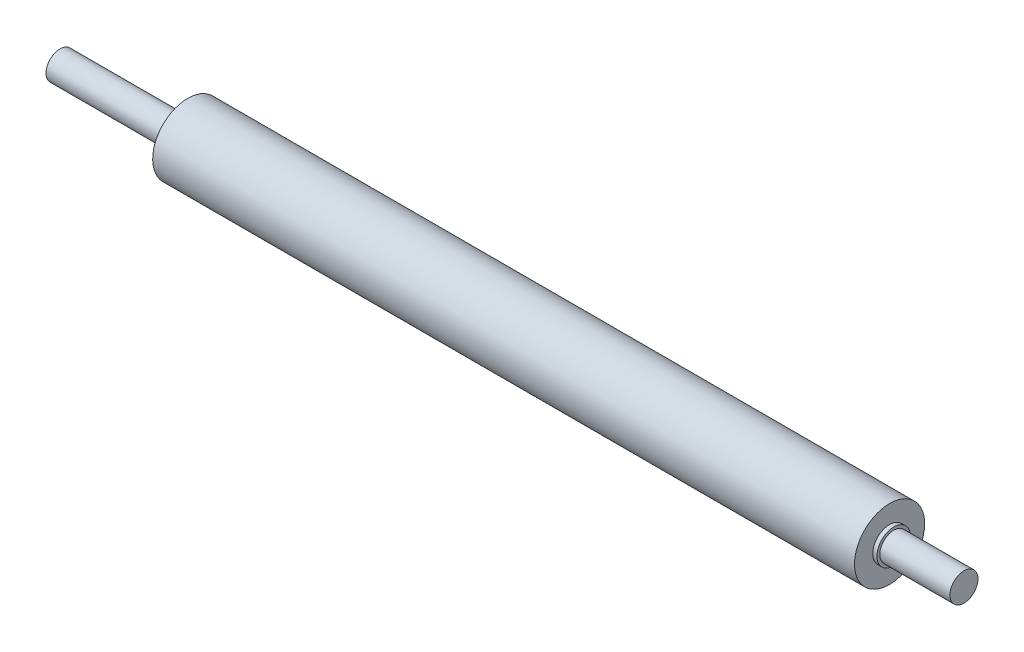
SolidWorks part; units mm, degrees
ref_plane "前视基准面" through (0, 0, 0) normal (0, 0, 1) x (1, 0, 0)
ref_plane "上视基准面" through (0, 0, 0) normal (0, 1, 0) x (1, 0, 0)
ref_plane "右视基准面" through (0, 0, 0) normal (1, 0, 0) x (0, 0, -1)
sketch "草图1" plane through (0, 0, 0) normal (0, 0, 1) x (1, 0, 0)
  line L0 (0, 0) -> (-265, 0) construction
  line L1 (-265, 0) -> (-265, 10)
  line L2 (-265, 10) -> (-253, 10)
  line L3 (-253, 10) -> (-253, 12)
  line L4 (-253, 12) -> (-250, 12)
  line L5 (-250, 12) -> (-250, 25)
  line L6 (-250, 25) -> (250, 25)
  line L7 (303, 0) -> (-265, 0)
  line L8 (247, 22) -> (-247, 22)
  line L9 (-247, 22) -> (-247, 12)
  line L10 (-247, 12) -> (247, 12)
  line L11 (0, 0) -> (0, 24) construction
  line L12 (247, 22) -> (247, 12)
  line L13 (250, 12) -> (250, 25)
  line L14 (253, 12) -> (250, 12)
  line L15 (253, 10) -> (253, 12)
  line L16 (303, 10) -> (253, 10)
  line L17 (303, 0) -> (303, 10)
  point P20 (0, 12)
  dimension "D1" = 12
  dimension "D2" = 3
  dimension "D3" = 2
  dimension "D4" = 500
  dimension "D5" = 12
  dimension "D6" = 20
  dimension "D7" = 3
  dimension "D8" = 50
  dimension "D9" = 3
  dimension "D10" = 50
revolve "旋转1" add sketch "草图1" angle 360 about L7
sketch "草图2" plane through (-265, 0, 0) normal (-1, 0, 0) x (0, 0, 1)
  circle A1 centre (0, 0) radius 10
  circle A2 centre (0, 0) radius 10
  dimension "D1" = 0
extrude "凸台-拉伸1" add sketch "草图2" along normal blind 76
